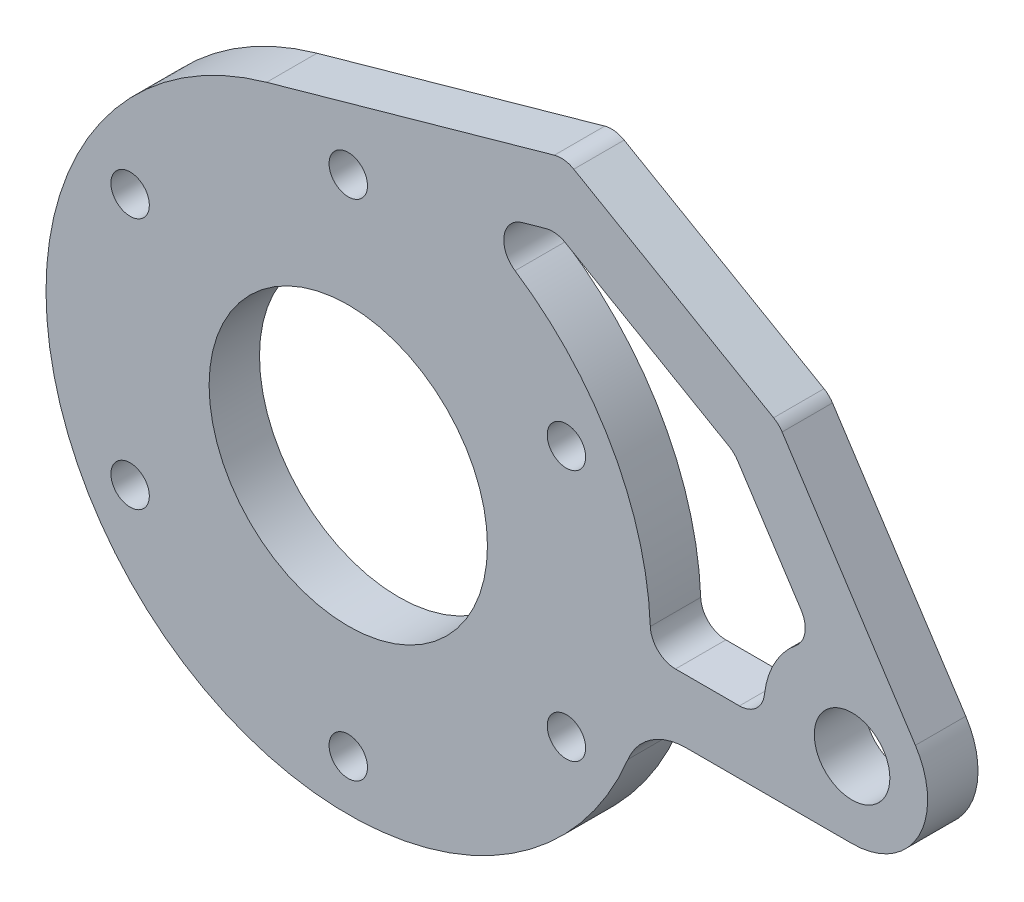
SolidWorks part; units mm, degrees
material "Thornel Mat VMA"
ref_plane "前视基准面" through (0, 0, 0) normal (0, 0, 1) x (1, 0, 0)
ref_plane "上视基准面" through (0, 0, 0) normal (0, 1, 0) x (1, 0, 0)
ref_plane "右视基准面" through (0, 0, 0) normal (1, 0, 0) x (0, 0, -1)
other "Configuration Table"
sketch "草图1" plane through (0, 0, 0) normal (0, 0, 1) x (1, 0, 0)
  circle A0 centre (0, 0) radius 11.05
  circle A1 centre (0, 0) radius 20 construction
  circle A2 centre (0, 0) radius 24
  dimension "D1" = 22.1
  dimension "D2" = 40
  dimension "D3" = 4
extrude "凸台-拉伸1" add sketch "草图1" along normal blind 4
sketch "草图2" plane through (0, 0, 4) normal (0, 0, 1) x (1, 0, 0)
  line L0 (0, 0) -> (40, 0) construction
  line L1 (40, 6) -> (23.2379, 6)
  line L2 (40, -6) -> (23.2379, -6)
  circle A0 centre (40, 0) radius 3
  arc A1 (40, -6) -> (40, 6) centre (40, 0) ccw
  circle A2 centre (0, 0) radius 24 construction
  arc A3 (23.2379, -6) -> (23.2379, 6) centre (0, 0) ccw
  dimension "D2" = 6
  dimension "D3" = 3
  dimension "D1" = 40
extrude "凸台-拉伸2" add sketch "草图2" against normal up to surface (4 mm away) up to face at (24, 0, 0)
sketch "草图3" plane through (0, 0, 4) normal (0, 0, 1) x (1, 0, 0)
  line L1 (34.1853, 19.9271) -> (17.175, 29.748)
  line L2 (17.175, 29.748) -> (-6.4855, 23.1071)
  line L3 (34.1853, 19.9271) -> (45.0281, 3.2738)
  line L4 (40, 6) -> (23.2379, 6) construction
  line L5 (40, 6) -> (23.2379, 6)
  arc A0 (23.2379, 6) -> (23.2379, -6) centre (0, 0) ccw construction
  arc A1 (40, -6) -> (40, 6) centre (40, 0) ccw construction
  arc A4 (45.0281, 3.2738) -> (40, 6) centre (40, 0) ccw
  arc A5 (23.2379, 6) -> (-6.4855, 23.1071) centre (0, 0) ccw
  dimension "D1" = 17.175
  dimension "D2" = 29.748
  dimension "D3" = 19.9271
  dimension "D4" = 34.1853
extrude "凸台-拉伸3" add sketch "草图3" against normal up to surface (4 mm away) up to face at (21.3095, 0, 0)
fillet "圆角1" radius 2 2 edges at (34.1853, 19.9271, 2) (17.175, 29.748, 2)
fillet "圆角2" radius 5 1 edges at (23.2379, -6, 2)
sketch "草图4" plane through (0, 0, 4) normal (0, 0, 1) x (1, 0, 0)
  circle A0 centre (0, 0) radius 20 construction
  circle A1 centre (0, 20) radius 1.525
  circle A2 centre (17.3205, 10) radius 1.525
  circle A3 centre (17.3205, -10) radius 1.525
  circle A4 centre (0, -20) radius 1.525
  circle A5 centre (-17.3205, -10) radius 1.525
  circle A6 centre (-17.3205, 10) radius 1.525
  point P5 (-12.041, -23.2964)
  point P6 (0, 0)
  point P17 (0, 0)
  dimension "D1" = 40
  dimension "D2" = 3.05
  dimension "D3" = 6
extrude "切除-拉伸1" cut sketch "草图4" against normal up to surface (4 mm away) up to face at (22.9591, 8.9171, 0)
sketch "草图5" plane through (0, 0, 4) normal (0, 0, 1) x (1, 0, 0)
  line L0 (8.983, 22.2555) -> (16.4987, 24.3649)
  line L1 (16.4987, 24.3649) -> (30.6484, 16.1956)
  line L2 (30.6484, 16.1956) -> (37.0578, 6.3516)
  line L3 (45.0281, 3.2738) -> (34.4466, 19.5258) construction
  line L4 (33.7705, 20.1665) -> (17.9045, 29.3268) construction
  line L5 (16.364, 29.5204) -> (-6.4855, 23.1071) construction
  line L6 (23.9792, -1) -> (33.0718, -1)
  line L7 (26.8328, -6) -> (40, -6) construction
  arc A0 (23.9792, -1) -> (8.983, 22.2555) centre (0, 0) ccw
  arc A1 (37.0578, 6.3516) -> (33.0718, -1) centre (40, 0) ccw
  circle A2 centre (40, 0) radius 3 construction
  dimension "D1" = 48
  dimension "D2" = 4
  dimension "D3" = 5
  dimension "D4" = 5
  dimension "D5" = 5
  dimension "D6" = 5
extrude "切除-拉伸2" cut sketch "草图5" against normal up to surface (4 mm away) up to face at (1.525, 20, 0)
fillet "圆角3" radius 2 6 edges at (16.4987, 24.3649, 2) (30.6484, 16.1956, 2) (37.0578, 6.3516, 2) (8.983, 22.2555, 2) (23.9792, -1, 2) (33.0718, -1, 2)
